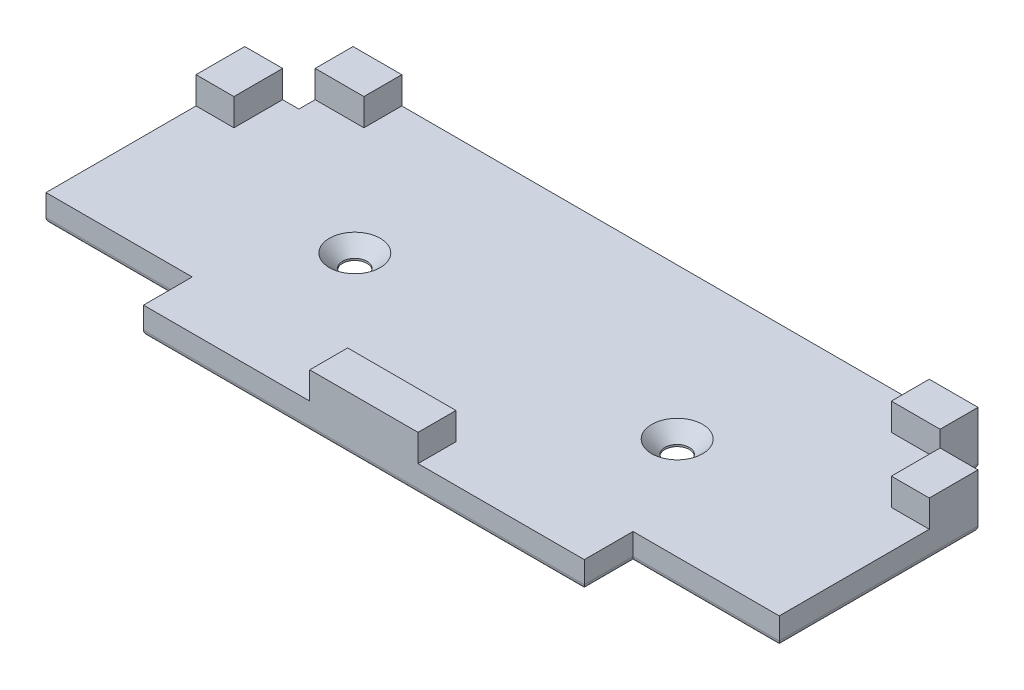
SolidWorks part; units mm, degrees
ref_plane "Front Plane" through (0, 0, 0) normal (0, 0, 1) x (1, 0, 0)
ref_plane "Top Plane" through (0, 0, 0) normal (0, 1, 0) x (1, 0, 0)
ref_plane "Right Plane" through (0, 0, 0) normal (1, 0, 0) x (0, 0, -1)
sketch "Sketch1" plane through (0, 0, 0) normal (0, 1, 0) x (1, 0, 0)
  line L0 (67.7, 27.85) -> (-67.7, 27.85)
  line L1 (60.7, -20.85) -> (-60.7, -20.85) construction
  line L2 (60.7, -20.85) -> (60.7, 20.85) construction
  line L3 (60.7, 20.85) -> (-60.7, 20.85) construction
  line L4 (-60.7, -20.85) -> (-60.7, 20.85) construction
  line L5 (60.7, -20.85) -> (-60.7, 20.85) construction
  line L6 (60.7, 20.85) -> (-60.7, -20.85) construction
  line L7 (-67.7, -27.85) -> (-67.7, 27.85)
  line L8 (67.7, -27.85) -> (-67.7, -27.85)
  line L9 (67.7, -27.85) -> (67.7, 27.85)
  point P0 (0, 0)
  dimension "D1" = 41.7
  dimension "D2" = 121.4
  dimension "D3" = 7
extrude "Boss-Extrude1" add sketch "Sketch1" along normal blind 5
sketch "Sketch2" plane through (0, 5, 0) normal (0, 1, 0) x (1, 0, 0)
  line L1 (60.7, 20.85) -> (-60.7, 20.85) construction
  line L3 (-60.7, -20.85) -> (-60.7, 20.85) construction
  line L5 (-48.7, 20.85) -> (-60.7, 20.85)
  line L7 (-60.7, 8.85) -> (-60.7, 20.85)
  line L8 (-48.7, 20.85) -> (-48.7, 27.85)
  line L9 (67.7, 27.85) -> (-67.7, 27.85) construction
  line L10 (-48.7, 27.85) -> (-67.7, 27.85)
  line L11 (-67.7, 27.85) -> (-67.7, 8.85)
  line L12 (-67.7, -27.85) -> (-67.7, 27.85) construction
  line L13 (-67.7, 8.85) -> (-60.7, 8.85)
  line L14 (-60.7, 8.85) -> (-60.7, 20.85)
  line L15 (60.7, -20.85) -> (-60.7, -20.85) construction
  line L16 (-10, -27.85) -> (10, -27.85)
  line L17 (-10, -27.85) -> (-10, -20.85)
  line L18 (-10, -20.85) -> (10, -20.85)
  line L19 (10, -27.85) -> (10, -20.85)
  line L20 (-10, -27.85) -> (10, -20.85) construction
  line L21 (-10, -20.85) -> (10, -27.85) construction
  line L22 (67.7, -27.85) -> (-67.7, -27.85) construction
  line L23 (0, 0) -> (0, -24.35) construction
  line L24 (60.7, 8.85) -> (60.7, 20.85)
  line L25 (67.7, 8.85) -> (60.7, 8.85)
  line L26 (67.7, 27.85) -> (67.7, 8.85)
  line L27 (48.7, 27.85) -> (67.7, 27.85)
  line L28 (48.7, 20.85) -> (48.7, 27.85)
  line L29 (60.7, 8.85) -> (60.7, 20.85)
  line L30 (48.7, 20.85) -> (60.7, 20.85)
  point P0 (0, -24.35)
  line M8 (67.7, -27.85) -> (67.7, 27.85)
  line M9 (67.7, 27.85) -> (-67.7, 27.85)
  line M10 (-67.7, 27.85) -> (-67.7, -27.85)
  line M11 (-67.7, -27.85) -> (67.7, -27.85)
  dimension "D1" = 12
  dimension "D2" = 20
extrude "Boss-Extrude2" add sketch "Sketch2" along normal blind 5 contours L13 L7 L5 L8 M10 M9 | L19 L18 L17 M11 | L28 L30 L24 L25 M8 M9
sketch "Sketch3" plane through (0, 5, 0) normal (0, 1, 0) x (1, 0, 0)
  line L0 (-60.7, -20.85) -> (-60.7, 20.85) construction
  line L1 (-67.7, -27.85) -> (-40.7, -27.85)
  line L2 (-67.7, -27.85) -> (-67.7, -18.85)
  line L3 (-67.7, -18.85) -> (-40.7, -18.85)
  line L4 (-40.7, -27.85) -> (-40.7, -18.85)
  dimension "D1" = 9
  dimension "D2" = 20
extrude "Cut-Extrude1" cut sketch "Sketch3" against normal through all
mirror "Mirror1" about plane through (0, 0, 0) normal (1, 0, 0) of "Cut-Extrude1"
sketch "Sketch4" plane through (0, 5, 0) normal (0, -1, 0) x (1, 0, 0)
  line L0 (0, 0) -> (-30, 0) construction
  line L1 (-30, 0) -> (0, 0) construction
  line L2 (0, 0) -> (30, 0) construction
  point P5 (-30, 0)
  point P6 (30, 0)
  dimension "D1" = 30
hole_wizard "CSK for M4 Countersunk Flat Head1" positions "3DSketch2" profile "Sketch6" countersink size "M4" standard "BSI" end condition through all
sketch3d "3DSketch2"
  line L0 (0, 5, 0) -> (-30, 5, 0) construction
  point P0 (-29.5278, 5, 0)
  point P4 (30, 5, 0)
sketch "Sketch6" plane through (-29.5278, 5, 0) normal (1, 0, 0) x (0, 0, 1)
  line L0 (0, 0) -> (0, 5)
  line L1 (0, 5) -> (2.25, 5)
  line L2 (2.25, 5) -> (2.25, 2.45)
  line L3 (2.25, 2.45) -> (4.7, 0)
  line L5 (4.7, 0) -> (0, 0)
  line L6 (-2.25, 2.45) -> (-4.7, 0) construction
  line L11 (0, -6.35) -> (0, 107.95) construction
  dimension "Thru Hole Dia." = 4.5
  dimension "Thru Hole Depth" = 5
  dimension "Near C'Sink Dia." = 9.4
  dimension "Near C'Sink Angle" = 90
sketch "Sketch7" plane through (0, 0, 0) normal (0, -1, 0) x (1, 0, 0)
  line L1 (-45, -15) -> (-15, -15)
  line L2 (-45, -15) -> (-45, 15)
  line L3 (-45, 15) -> (-15, 15)
  line L4 (-15, -15) -> (-15, 15)
  line L5 (-45, -15) -> (-15, 15) construction
  line L6 (-45, 15) -> (-15, -15) construction
  line L7 (15, -15) -> (45, -15)
  line L8 (15, -15) -> (15, 15)
  line L9 (15, 15) -> (45, 15)
  line L10 (45, -15) -> (45, 15)
  line L11 (15, -15) -> (45, 15) construction
  line L12 (15, 15) -> (45, -15) construction
  point P0 (-30, 0)
  point P6 (30, 0)
  dimension "D1" = 30
extrude "Cut-Extrude2" cut sketch "Sketch7" against normal blind 2.2
sketch "Sketch8" plane through (67.7, 0, 0) normal (1, 0, 0) x (0, 0, -1)
  line L0 (0, 0) -> (22, 0) construction
  line L1 (-18.85, 0) -> (27.85, 0) construction
  line L2 (0, 0) -> (22, 0) construction
  line L3 (-27.85, 0) -> (-18.85, 0) construction
  line L4 (0, 0) -> (0, 5) construction
  line L5 (19.5, -10) -> (24.5, -10)
  line L6 (19.5, -10) -> (19.5, 10)
  line L7 (19.5, 10) -> (24.5, 10)
  line L8 (24.5, -10) -> (24.5, 10)
  line L9 (19.5, -10) -> (24.5, 10) construction
  line L10 (19.5, 10) -> (24.5, -10) construction
  line L11 (-18.85, 5) -> (8.85, 5) construction
  dimension "D1" = 22
  dimension "D2" = 10
  dimension "D3" = 5
sketch "Sketch9" plane through (0, 10, 0) normal (0, 1, 0) x (1, 0, 0)
  line L1 (67.7, 27.85) -> (57.7, 27.85)
  line L2 (67.7, 27.85) -> (67.7, 17.85)
  line L3 (67.7, 17.85) -> (57.7, 17.85)
  line L4 (57.7, 27.85) -> (57.7, 17.85)
  dimension "D1" = 10
  dimension "D2" = 10
extrude "Cut-Extrude5" cut sketch "Sketch9" against normal through all
mirror "Mirror2" about plane through (0, 0, 0) normal (1, 0, 0) of "Cut-Extrude5"
fillet "Fillet1" radius 1 12 edges at (-57.7, 0, -22.85) (-62.7, 0, -17.85) (-67.7, 0, 0.5) (-54.2, 0, 18.85) (-40.7, 0, 23.35) (40.7, 0, 23.35) (0, 0, 27.85) (0, 0, -27.85) (57.7, 0, -22.85) (62.7, 0, -17.85) (54.2, 0, 18.85) (67.7, 0, 0.5)
